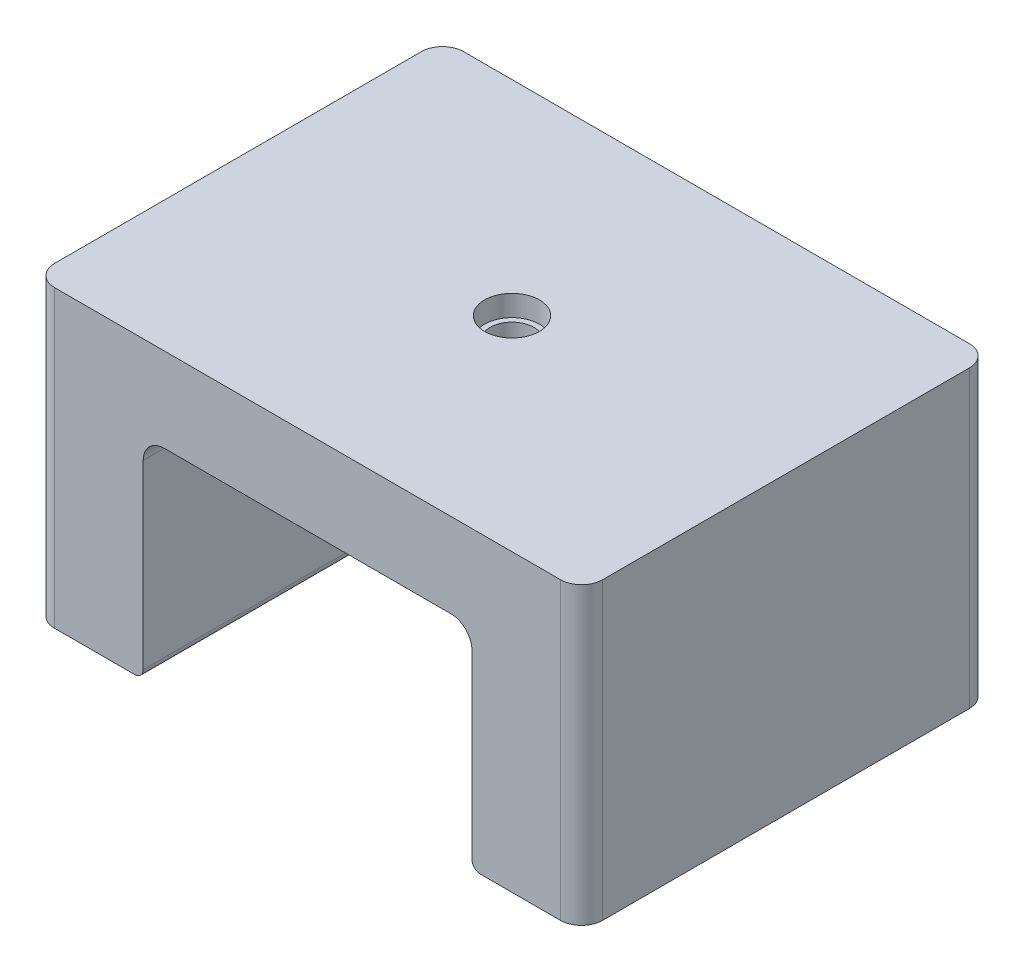
SolidWorks part; units mm, degrees
material "K110"
ref_plane "Front Plane" through (0, 0, 0) normal (0, 0, 1) x (1, 0, 0)
ref_plane "Top Plane" through (0, 0, 0) normal (0, 1, 0) x (1, 0, 0)
ref_plane "Right Plane" through (0, 0, 0) normal (1, 0, 0) x (0, 0, -1)
sketch "Sketch1" plane through (0, 0, 0) normal (0, 1, 0) x (1, 0, 0)
  line L0 (-65, -48.5) -> (-65, 48.5)
  line L7 (-65, 48.5) -> (65, 48.5)
  line L8 (65, -48.5) -> (65, 48.5)
  line L9 (-65, -48.5) -> (65, -48.5)
  point P0 (0, 0)
  point P10 (0, -48.5)
  point P11 (-65, 0)
  dimension "D3" = 97
  dimension "D4" = 130
extrude "Boss-Extrude1" add sketch "Sketch1" along normal blind 70
sketch "Sketch2" plane through (0, 0, 48.5) normal (0, 0, 1) x (1, 0, 0)
  line L0 (-65, 0) -> (65, 0) construction
  line L1 (-39, 0) -> (39, 0)
  line L2 (-39, 0) -> (-39, 50)
  line L3 (-39, 50) -> (39, 50)
  line L4 (39, 0) -> (39, 50)
  dimension "D1" = 78
  dimension "D2" = 50
extrude "Cut-Extrude1" cut sketch "Sketch2" against normal through all
fillet "Fillet3" radius 5 2 edges at (39, 50, 0) (-39, 50, 0)
sketch "Sketch3" plane through (0, 70, 0) normal (0, 1, 0) x (1, 0, 0)
  circle A0 centre (0, 0) radius 5.2
  dimension "D1" = 10.4
extrude "Cut-Extrude2" cut sketch "Sketch3" against normal through all
sketch "Sketch4" plane through (0, 70, 0) normal (0, 1, 0) x (1, 0, 0)
  circle A0 centre (0, 0) radius 6.5
  dimension "D1" = 13
extrude "Cut-Extrude3" cut sketch "Sketch4" against normal blind 5
fillet "Fillet2" radius 5 4 edges at (-65, 35, -48.5) (-65, 35, 48.5) (65, 35, -48.5) (65, 35, 48.5)
fillet "Fillet4" radius 2 2 edges at (39, 0, 0) (-39, 0, 0)
